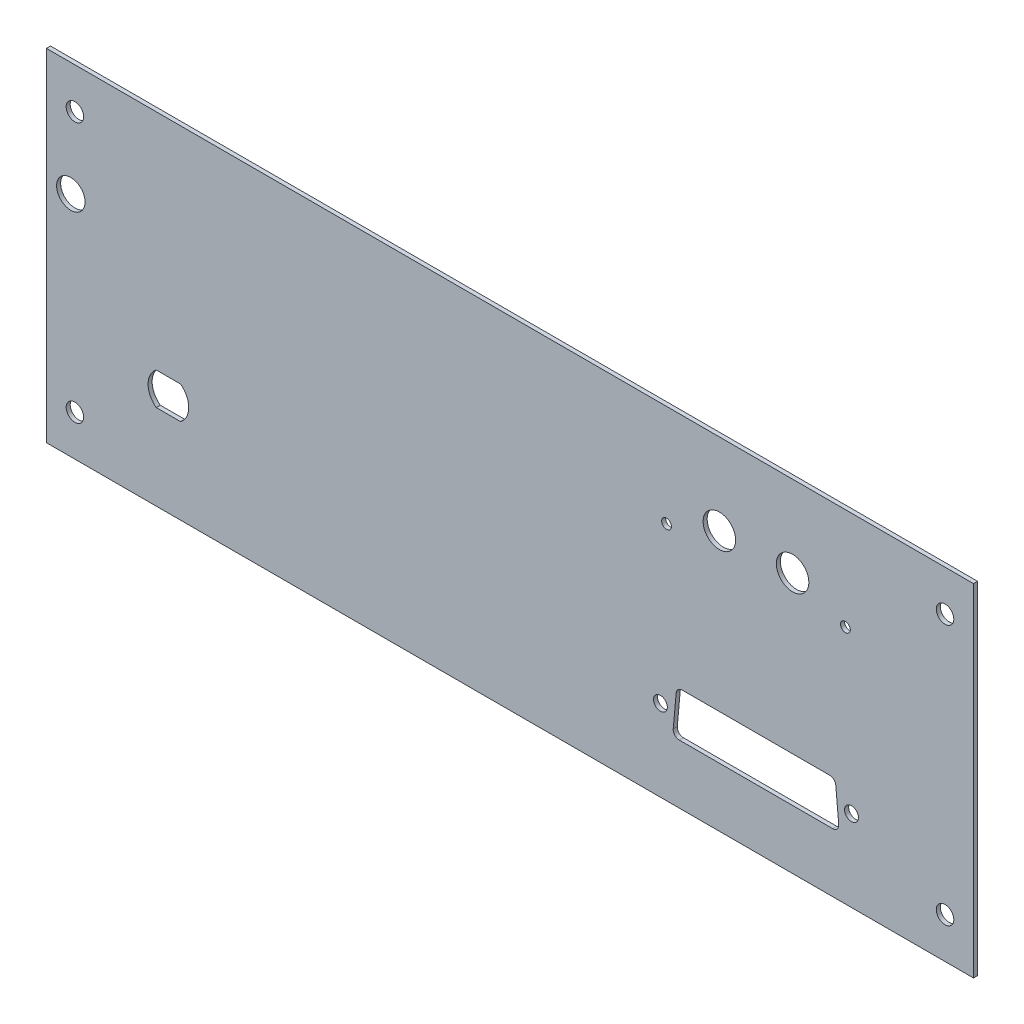
SolidWorks part; units mm, degrees
ref_plane "Спереди" through (0, 0, 0) normal (0, 0, 1) x (1, 0, 0)
ref_plane "Сверху" through (0, 0, 0) normal (0, 1, 0) x (1, 0, 0)
ref_plane "Справа" through (0, 0, 0) normal (1, 0, 0) x (0, 0, -1)
sketch "Эскиз1" plane through (0, 0, 0) normal (0, 0, 1) x (1, 0, 0)
  line L0 (0, 0) -> (58.061, 0) construction
  line L1 (0, 0) -> (0, 47.3035) construction
  line L3 (-114, -42) -> (114, -42)
  line L4 (-114, -42) -> (-114, 42)
  line L5 (-114, 42) -> (114, 42)
  line L6 (114, -42) -> (114, 42)
  circle A8 centre (107, 32) radius 2.15
  circle A9 centre (-107, 32) radius 2.15
  circle A10 centre (-107, -32) radius 2.15
  circle A11 centre (107, -32) radius 2.15
  dimension "D14" = 4.3
  dimension "D15" = 10
  dimension "D16" = 7
  dimension "D1" = 84
  dimension "D2" = 228
extrude "Вытянуть1" add sketch "Эскиз1" along normal blind 1
sketch "Эскиз3" plane through (0, 0, 1) normal (0, 0, 1) x (1, 0, 0)
  line L0 (-47.9981, -22) -> (120.6827, -22) construction
  line L1 (40.1487, -25.8642) -> (40.876, -17.8642)
  line L2 (41.6425, -27.5) -> (79.3575, -27.5)
  line L3 (-114, -42) -> (114, -42) construction
  line L4 (42.3698, -16.5) -> (78.6302, -16.5)
  line L5 (34.3104, 17) -> (86.5925, 17) construction
  line L6 (80.8513, -25.8642) -> (80.124, -17.8642)
  line L7 (60.5, 95.3032) -> (60.5, -77.6913) construction
  line L10 (51.5, 22) -> (68.5193, 22) construction
  line L11 (114, -42) -> (114, 42) construction
  line L12 (114, 42) -> (-114, 42) construction
  circle A0 centre (37, -22) radius 1.7
  circle A1 centre (84, -22) radius 1.7
  arc A2 (41.6425, -27.5) -> (40.1487, -25.8642) centre (41.6425, -26) cw
  arc A3 (42.3698, -16.5) -> (40.876, -17.8642) centre (42.3698, -18) ccw
  arc A4 (80.124, -17.8642) -> (78.6302, -16.5) centre (78.6302, -18) ccw
  arc A5 (79.3575, -27.5) -> (80.8513, -25.8642) centre (79.3575, -26) ccw
  circle A6 centre (38.5, 17) radius 1.2
  circle A7 centre (82.5, 17) radius 1.2
  circle A8 centre (51.5, 22) radius 4
  circle A9 centre (69.5, 22) radius 4
  point P14 (40, -27.5)
  point P17 (41, -16.5)
  point P20 (80, -16.5)
  point P23 (81, -27.5)
  dimension "D4" = 47
  dimension "D5" = 3.4
  dimension "D6" = 1.5
  dimension "D9" = 2.4
  dimension "D11" = 18
  dimension "D12" = 8
  dimension "D13" = 44
  dimension "D14" = 20
  dimension "D8" = 30
  dimension "D1" = 39
  dimension "D2" = 41
  dimension "D3" = 11
  dimension "D7" = 20
  dimension "D10" = 25
extrude "Вырез-Вытянуть1" cut sketch "Эскиз3" against normal blind 10
cosmetic thread "Условное изображение резьбы1" parameters "D2"=3
cosmetic thread "Условное изображение резьбы2" parameters "D2"=3
sketch "Эскиз4" plane through (0, 0, 1) normal (0, 0, 1) x (1, 0, 0)
  line L0 (-114, 42) -> (-114, -42) construction
  line L1 (-114, -42) -> (114, -42) construction
  line L2 (-84, -17) -> (-92.3635, -17) construction
  line L3 (-87, -13) -> (-81, -13)
  line L4 (-87, -21) -> (-81, -21)
  circle A0 centre (-108, 14) radius 3.5
  arc A1 (-87, -13) -> (-87, -21) centre (-84, -17) ccw
  arc A2 (-81, -21) -> (-81, -13) centre (-84, -17) ccw
  dimension "D3" = 7
  dimension "D6" = 10
  dimension "D1" = 6
  dimension "D2" = 56
  dimension "D4" = 25
  dimension "D5" = 30
  dimension "D7" = 4
extrude "Вырез-Вытянуть2" cut sketch "Эскиз4" against normal blind 1
